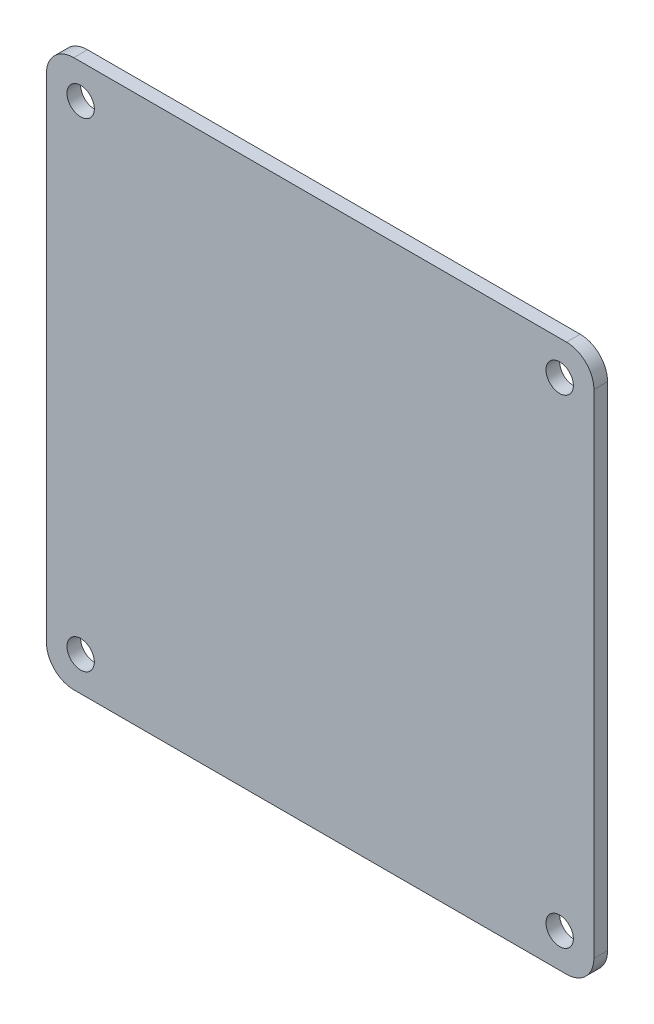
SolidWorks part; units mm, degrees
ref_plane "Front Plane" through (0, 0, 0) normal (0, 0, 1) x (1, 0, 0)
ref_plane "Top Plane" through (0, 0, 0) normal (0, 1, 0) x (1, 0, 0)
ref_plane "Right Plane" through (0, 0, 0) normal (1, 0, 0) x (0, 0, -1)
sketch "Sketch1" plane through (0, 0, 0) normal (0, 0, 1) x (1, 0, 0)
  line L1 (-96.52, 0) -> (-5.08, 0)
  line L2 (-101.6, 5.08) -> (-101.6, 96.52)
  line L3 (-96.52, 101.6) -> (-5.08, 101.6)
  line L4 (0, 5.08) -> (0, 96.52)
  arc A0 (-5.08, 0) -> (0, 5.08) centre (-5.08, 5.08) ccw
  arc A1 (0, 96.52) -> (-5.08, 101.6) centre (-5.08, 96.52) ccw
  arc A2 (-96.52, 101.6) -> (-101.6, 96.52) centre (-96.52, 96.52) ccw
  arc A3 (-96.52, 0) -> (-101.6, 5.08) centre (-96.52, 5.08) cw
  dimension "D3" = 5.08
sketch "Sketch4" plane through (0, 0, 0) normal (0, 0, 1) x (1, 0, 0)
  circle A0 centre (-95.25, 6.35) radius 2.54
  circle A4 centre (-6.35, 6.35) radius 2.54
  circle A5 centre (-6.35, 95.25) radius 2.54
  circle A6 centre (-95.25, 95.25) radius 2.54
extrude "Boss-Extrude1" add sketch "Sketch1" along normal blind 2.54
extrude "Cut-Extrude2" cut sketch "Sketch4" along normal blind 2.54
